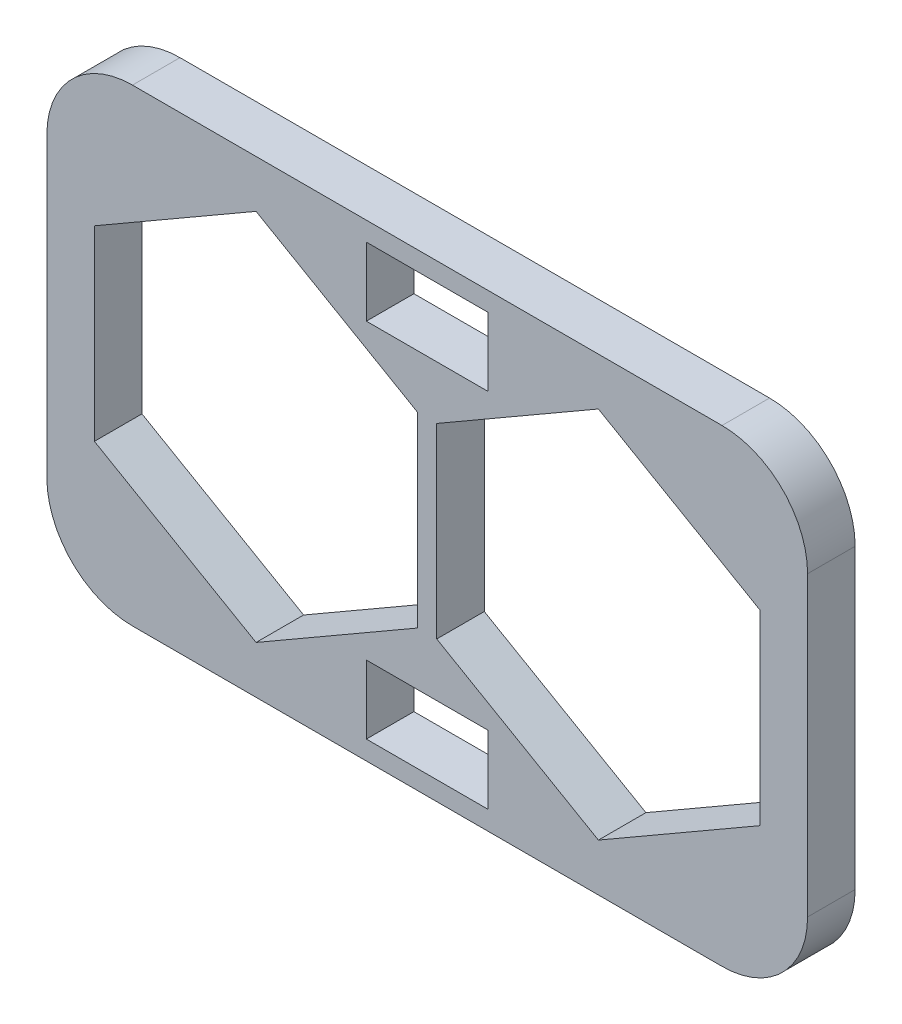
SolidWorks part; units mm, degrees
ref_plane "Front Plane" through (0, 0, 0) normal (0, 0, 1) x (1, 0, 0)
ref_plane "Top Plane" through (0, 0, 0) normal (0, 1, 0) x (1, 0, 0)
ref_plane "Right Plane" through (0, 0, 0) normal (1, 0, 0) x (0, 0, -1)
sketch "Sketch1" plane through (0, 0, 0) normal (0, 0, 1) x (1, 0, 0)
  line L0 (12.065, -6.2325) -> (22.86, -12.465)
  line L7 (-10.795, -6.2325) -> (0, -12.465)
  line L8 (0, -12.465) -> (10.795, -6.2325)
  line L9 (10.795, -6.2325) -> (10.795, 6.2325)
  line L10 (10.795, 6.2325) -> (0, 12.465)
  line L11 (0, 12.465) -> (-10.795, 6.2325)
  line L12 (-10.795, 6.2325) -> (-10.795, -6.2325)
  line L13 (22.86, -12.465) -> (33.655, -6.2325)
  line L14 (33.655, -6.2325) -> (33.655, 6.2325)
  line L15 (33.655, 6.2325) -> (22.86, 12.465)
  line L16 (22.86, 12.465) -> (12.065, 6.2325)
  line L17 (12.065, 6.2325) -> (12.065, -6.2325)
  line L24 (0, 0) -> (0, 12.465) construction
  line L49 (-8.255, 12.465) -> (31.115, 12.465)
  line L50 (-10.795, 9.925) -> (-10.795, -9.925)
  line L51 (-8.255, -12.465) -> (31.115, -12.465)
  line L52 (33.655, 9.925) -> (33.655, -9.925)
  line L53 (-8.255, 15.64) -> (31.115, 15.64)
  line L54 (36.83, 9.925) -> (36.83, -9.925)
  line L55 (-8.255, -15.64) -> (31.115, -15.64)
  line L56 (-13.97, 9.925) -> (-13.97, -9.925)
  line L57 (10.795, 6.2325) -> (12.065, 6.2325) construction
  line L59 (11.43, 6.2325) -> (11.43, 15.64) construction
  line L62 (7.366, 14.37) -> (15.494, 14.37)
  line L63 (7.366, 14.37) -> (7.366, 9.798)
  line L64 (7.366, 9.798) -> (15.494, 9.798)
  line L65 (15.494, 14.37) -> (15.494, 9.798)
  line L69 (0, 0) -> (-13.97, 0) construction
  line L114 (7.366, 14.37) -> (7.366, 9.798)
  line L129 (7.366, -9.798) -> (15.494, -9.798)
  line L130 (15.494, -14.37) -> (15.494, -9.798)
  line L131 (7.366, -14.37) -> (15.494, -14.37)
  line L132 (7.366, -14.37) -> (7.366, -9.798)
  circle A0 centre (0, 0) radius 7.5565
  circle A1 centre (0, 0) radius 10.795 construction
  circle A2 centre (22.86, 0) radius 7.5565
  circle A3 centre (22.86, 0) radius 10.795 construction
  arc A7 (-8.255, 12.465) -> (-10.795, 9.925) centre (-8.255, 9.925) ccw
  arc A13 (33.655, 9.925) -> (31.115, 12.465) centre (31.115, 9.925) ccw
  arc A14 (-10.795, -9.925) -> (-8.255, -12.465) centre (-8.255, -9.925) ccw
  arc A15 (33.655, -9.925) -> (31.115, -12.465) centre (31.115, -9.925) cw
  arc A16 (36.83, 9.925) -> (31.115, 15.64) centre (31.115, 9.925) ccw
  arc A17 (36.83, -9.925) -> (31.115, -15.64) centre (31.115, -9.925) cw
  arc A18 (-13.97, -9.925) -> (-8.255, -15.64) centre (-8.255, -9.925) ccw
  arc A19 (-8.255, 15.64) -> (-13.97, 9.925) centre (-8.255, 9.925) ccw
  point P0 (0, 0)
  point P8 (22.86, 0)
  point P9 (11.43, 14.37)
  point P57 (-45.72, 0)
  dimension "D1" = 15.113
  dimension "D8" = 3.175
  dimension "D5" = 2.54
  dimension "D6" = 2.54
  dimension "D7" = 2.54
  dimension "D2" = 21.59
  dimension "D4" = 22.86
  dimension "D9" = 24.93
  dimension "D10" = 1.27
  dimension "D11" = 8.128
  dimension "D13" = 4.572
  dimension "D3" = 2
extrude "Boss-Extrude1" add sketch "Sketch1" along normal blind 3.175
